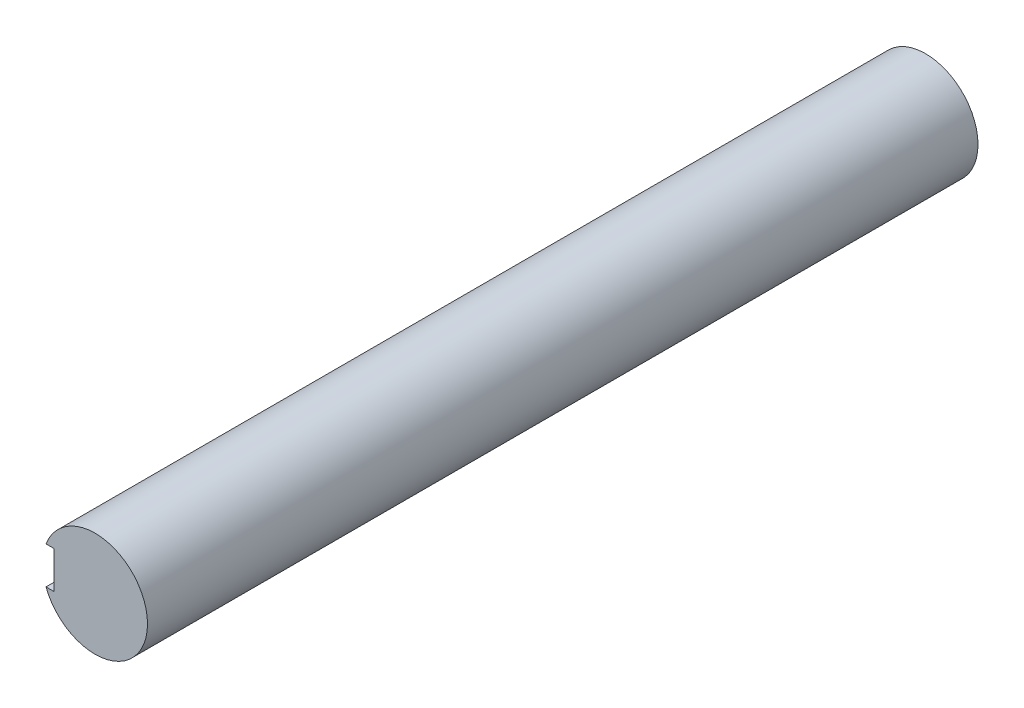
SolidWorks part; units mm, degrees
ref_plane "Front Plane" through (0, 0, 0) normal (0, 0, 1) x (1, 0, 0)
ref_plane "Top Plane" through (0, 0, 0) normal (0, 1, 0) x (1, 0, 0)
ref_plane "Right Plane" through (0, 0, 0) normal (1, 0, 0) x (0, 0, -1)
sketch "Sketch1" plane through (0, 0, 0) normal (0, 0, 1) x (1, 0, 0)
  circle A0 centre (-78.6475, -368.8222) radius 6
  dimension "D1" = 12
extrude "Boss-Extrude1" add sketch "Sketch1" along normal blind 85 and the other way blind 10
sketch "Sketch2" plane through (0, 0, 85) normal (0, 0, 1) x (1, 0, 0)
  line L0 (-72.6475, -368.8222) -> (-84.6475, -368.8222) construction
  line L1 (-85.5456, -370.9519) -> (-83.3424, -370.9519)
  line L2 (-85.5456, -370.9519) -> (-85.5456, -366.6925)
  line L3 (-85.5456, -366.6925) -> (-83.3424, -366.6925)
  line L4 (-83.3424, -370.9519) -> (-83.3424, -366.6925)
  circle A0 centre (-78.6475, -368.8222) radius 6 construction
extrude "Cut-Extrude1" cut sketch "Sketch2" against normal blind 80
